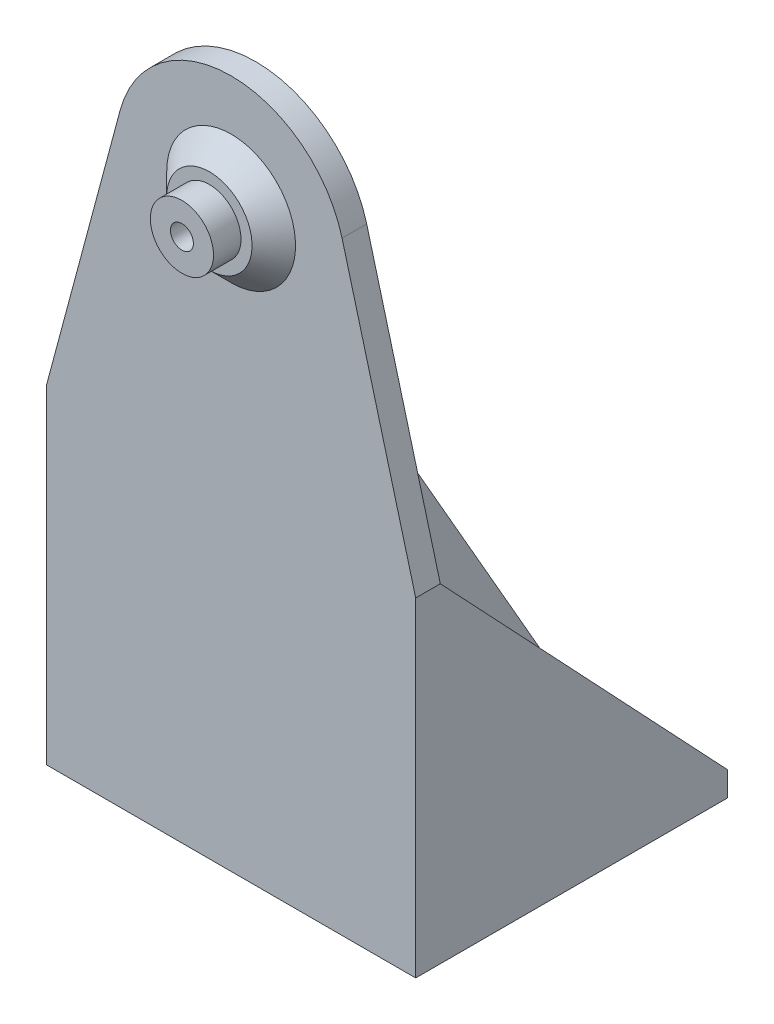
SolidWorks part; units mm, degrees
ref_plane "前视基准面" through (0, 0, 0) normal (0, 0, 1) x (1, 0, 0)
ref_plane "上视基准面" through (0, 0, 0) normal (0, 1, 0) x (1, 0, 0)
ref_plane "右视基准面" through (0, 0, 0) normal (1, 0, 0) x (0, 0, -1)
other "Configuration Table"
sketch "草图1" plane through (0, 0, 0) normal (0, 0, 1) x (1, 0, 0)
  circle A0 centre (0, 0) radius 1.4
  circle A1 centre (0, 0) radius 3.85
  dimension "D1" = 7.7
  dimension "D2" = 2.8
extrude "凸台-拉伸1" add sketch "草图1" against normal blind 3.35 contours A0 | A1
ref_plane "基准面1" through (0, 0, -3.35) normal (0, 0, -1) x (-1, 0, 0)
sketch "草图2" plane through (0, 0, -3.35) normal (0, 0, -1) x (-1, 0, 0)
  circle A0 centre (0, 0) radius 5.2
  dimension "D1" = 10.4
ref_plane "基准面2" through (0, 0, -6) normal (0, 0, -1) x (-1, 0, 0)
sketch "草图3" plane through (0, 0, -6) normal (0, 0, -1) x (-1, 0, 0)
  circle A0 centre (0, 0) radius 7.85
  dimension "D1" = 15.7
loft "放样1" add profiles "草图3", "草图2"
sketch "草图6" plane through (0, 0, -6) normal (0, 0, -1) x (-1, 0, 0)
  line L1 (0, 0) -> (0, 14) construction
  line L5 (-22.4988, -29.8748) -> (-22.4988, -69.9948)
  line L6 (22.4988, -29.8748) -> (22.4988, -69.9948)
  line L7 (-22.4988, -69.9948) -> (22.4988, -69.9948)
  line L8 (13.523, 3.6235) -> (22.4988, -29.8748)
  line L9 (-13.523, 3.6235) -> (-22.4988, -29.8748)
  arc A0 (-13.523, 3.6235) -> (13.523, 3.6235) centre (0, 0) cw
  dimension "D1" = 14
  dimension "D2" = 14
  dimension "D3" = 34.68
  dimension "D7" = 34.68
  dimension "D8" = 40.12
  dimension "D9" = 40.12
extrude "凸台-拉伸2" add sketch "草图6" along normal blind 3
sketch "草图7" plane through (0, 0, -9) normal (0, 0, -1) x (-1, 0, 0)
  circle A1 centre (0, 0) radius 1.4
  dimension "D1" = 2.8
extrude "切除-拉伸1" cut sketch "草图7" against normal blind 23.35
sketch "草图11" plane through (0, 0, -9) normal (0, 0, -1) x (-1, 0, 0)
  line L0 (-22.4988, -66.9948) -> (22.4988, -66.9948)
  line L1 (-22.4988, -29.8748) -> (-22.4988, -69.9948) construction
  line L2 (22.4988, -69.9948) -> (22.4988, -29.8748) construction
  line L3 (-22.4988, -69.9948) -> (22.4988, -69.9948) construction
  line L9 (-13.523, 3.6235) -> (-22.4988, -29.8748)
  line L10 (-22.4988, -29.8748) -> (-22.4988, -69.9948)
  line L11 (-22.4988, -69.9948) -> (22.4988, -69.9948)
  line L12 (22.4988, -69.9948) -> (22.4988, -29.8748)
  line L13 (22.4988, -29.8748) -> (13.523, 3.6235)
  line L15 (-22.4988, -66.9948) -> (-22.4988, -69.9948)
  line L16 (-22.4988, -69.9948) -> (22.4988, -69.9948)
  line L17 (22.4988, -69.9948) -> (22.4988, -66.9948)
  arc A1 (13.523, 3.6235) -> (-13.523, 3.6235) centre (0, 0) ccw
  dimension "D1" = 3
  dimension "D2" = 0
extrude "凸台-拉伸3" add sketch "草图11" along normal blind 35
ref_plane "基准面3" through (0, -66.9948, 0) normal (0, 1, 0) x (1, 0, 0)
sketch "草图14" plane through (0, -66.9948, 0) normal (0, 1, 0) x (1, 0, 0)
  line L0 (-14.0797, 35) -> (-14.0797, 19)
  line L1 (-22.4988, 44) -> (-22.4988, 9) construction
  line L2 (-22.4988, 44) -> (22.4988, 44) construction
  line L3 (-14.0797, 35) -> (-12.4814, 35) construction
  line L4 (-10.8831, 35) -> (-10.8831, 19)
  line L5 (0, 26.5) -> (0, 55.1831) construction
  line L6 (0, 55.1831) -> (0, -7.3456) construction
  line L7 (14.0797, 35) -> (14.0797, 19)
  line L8 (10.8831, 35) -> (10.8831, 19)
  arc A0 (-14.0797, 35) -> (-10.8831, 35) centre (-12.4814, 35) cw
  arc A1 (-10.8831, 19) -> (-14.0797, 19) centre (-12.4814, 19) cw
  arc A2 (10.8831, 19) -> (14.0797, 19) centre (12.4814, 19) ccw
  arc A3 (14.0797, 35) -> (10.8831, 35) centre (12.4814, 35) ccw
  dimension "D1" = 8.4191
  dimension "D2" = 16
  dimension "D3" = 9
  dimension "D4" = 1.5983
extrude "切除-拉伸4" cut sketch "草图14" against normal blind 35 contours L7 A3 L8 A2 | A1 L4 A0 L0
ref_plane "基准面4" through (22.4988, 0, 0) normal (1, 0, 0) x (0, 0, -1)
sketch "草图15" plane through (22.4988, 0, 0) normal (1, 0, 0) x (0, 0, -1)
  line L0 (9, -29.8748) -> (44, -66.9948)
  line L7 (6, -29.8748) -> (6, -69.9948)
  line L8 (6, -69.9948) -> (44, -69.9948)
  line L9 (44, -69.9948) -> (44, -66.9948)
  line L10 (44, -66.9948) -> (9, -66.9948)
  line L11 (9, -66.9948) -> (9, -29.8748)
  line L12 (9, -29.8748) -> (6, -29.8748)
  line L13 (6, -29.8748) -> (6, -69.9948)
  line L14 (6, -69.9948) -> (44, -69.9948)
  line L15 (44, -69.9948) -> (44, -66.9948)
  line L18 (9, -29.8748) -> (6, -29.8748)
  dimension "D1" = 0
extrude "凸台-拉伸4" add sketch "草图15" against normal blind 3
ref_plane "基准面5" through (0, 0, 0) normal (1, 0, 0) x (0, 0, -1)
mirror "镜向1" about plane through (0, 0, 0) normal (1, 0, 0) of "凸台-拉伸4"
sketch "草图19" plane through (0, 0, 0) normal (1, 0, 0) x (0, 0, -1)
  line L0 (44, -66.9948) -> (9, -6.0215)
  line L1 (9, 3.6235) -> (9, -29.8748) construction
  line L2 (9, -6.0215) -> (9, -66.9948)
  line L3 (55.1831, -66.9948) -> (-7.3456, -66.9948) construction
  line L4 (9, -66.9948) -> (44, -66.9948)
  dimension "D1" = 70.3047
extrude "凸台-拉伸5" add sketch "草图19" along normal blind 1.5 and the other way blind 1.5
